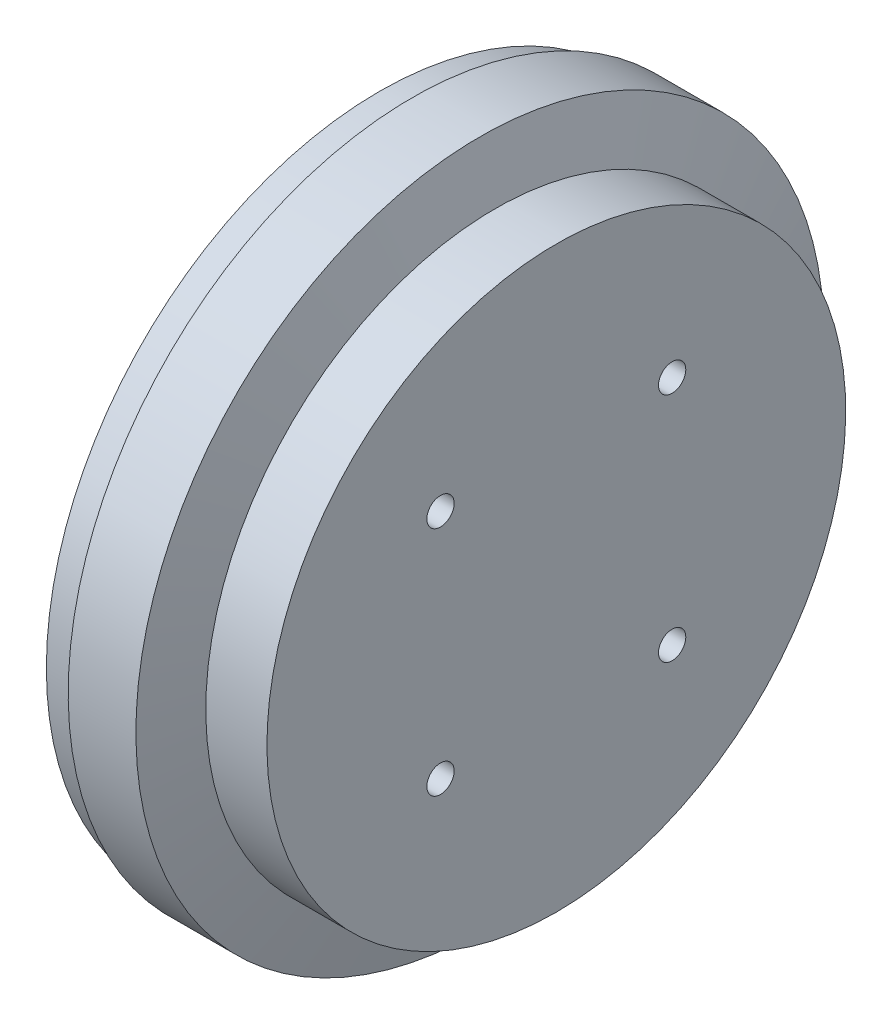
SolidWorks part; units mm, degrees
ref_plane "Front" through (0, 0, 0) normal (0, 0, 1) x (1, 0, 0)
ref_plane "Top" through (0, 0, 0) normal (0, 1, 0) x (1, 0, 0)
ref_plane "Right" through (0, 0, 0) normal (1, 0, 0) x (0, 0, -1)
sketch "Sketch1" plane through (0, 0, 0) normal (0, 0, 1) x (1, 0, 0)
  line L0 (-6.6, 0) -> (6.6, 0)
  line L1 (6.6, 0) -> (6.6, 26.5)
  line L2 (6.6, 26.5) -> (1, 26.5)
  line L3 (1, 26.5) -> (-0.4, 31.5)
  line L4 (-0.4, 31.5) -> (-6.6, 31.5)
  line L5 (-6.6, 31.5) -> (-6.6, 0)
  point P4 (0, 0)
  dimension "D1" = 26.5
  dimension "D2" = 5.6
  dimension "D3" = 1.4
  dimension "D4" = 31.5
  dimension "D5" = 6.2
revolve "Revolve1" add sketch "Sketch1" angle 360 about L0
sketch "Sketch2" plane through (6.6, 0, 0) normal (1, 0, 0) x (0, 0, -1)
  line L0 (-10.6066, -10.6066) -> (10.6066, 10.6066) construction
  line L1 (10.6066, -10.6066) -> (-10.6066, 10.6066) construction
  line L2 (0, 0) -> (0, 15) construction
  circle A0 centre (0, 0) radius 15 construction
  point P6 (0, 0)
  point P8 (0, 0)
  dimension "D1" = 30
  dimension "D2" = 45
hole_wizard "M3x0.5 Tapped Hole1" positions "Sketch3" profile "Sketch4" tap size "M3x0.5" standard "ANSI Metric"
sketch "Sketch3" plane through (6.6, 0, 0) normal (1, 0, 0) x (0, 0, -1)
  point P0 (-10.6066, 10.6066)
  point P3 (-10.6066, -10.6066)
  point P6 (10.6066, -10.6066)
  point P9 (10.6066, 10.6066)
sketch "Sketch4" plane through (6.6, 10.6066, 10.6066) normal (0, 1, 0) x (0, 0, -1)
  line L0 (0, 0) -> (0, 8.2511)
  line L1 (0, 8.2511) -> (1.25, 7.5)
  line L2 (1.25, 7.5) -> (1.25, 0)
  line L5 (1.25, 0) -> (0, 0)
  line L10 (0, 8.2511) -> (-1.25, 7.5) construction
  line L11 (0, -6.35) -> (0, 107.95) construction
  dimension "Tap Drill Dia." = 2.5
  dimension "Tap Drill Depth" = 7.5
  dimension "Drill Angle" = 118
cosmetic thread "Hole Thread1" parameters "D1"=6, "D2"=3
cosmetic thread "Hole Thread2" parameters "D1"=6, "D2"=3
cosmetic thread "Hole Thread3" parameters "D1"=6, "D2"=3
cosmetic thread "Hole Thread4" parameters "D1"=6, "D2"=3
sketch "Sketch5" plane through (-6.6, 0, 0) normal (-1, 0, 0) x (0, 0, 1)
  circle A0 centre (0, 0) radius 30.5
  circle A1 centre (0, 0) radius 31.5 construction
  dimension "D1" = 1
extrude "Boss-Extrude1" add sketch "Sketch5" along normal blind 3
